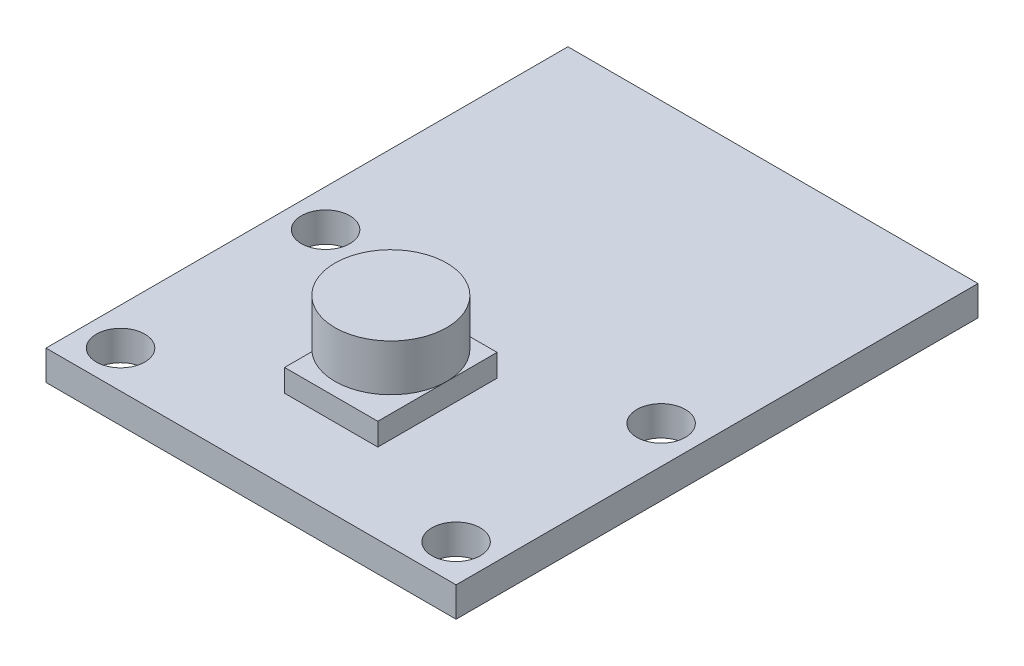
SolidWorks part; units mm, degrees
ref_plane "Plan de face" through (0, 0, 0) normal (0, 0, 1) x (1, 0, 0)
ref_plane "Plan de dessus" through (0, 0, 0) normal (0, 1, 0) x (1, 0, 0)
ref_plane "Plan de droite" through (0, 0, 0) normal (1, 0, 0) x (0, 0, -1)
sketch "Esquisse1" plane through (0, 0, 0) normal (0, 1, 0) x (1, 0, 0)
  line L0 (0, -7.5) -> (0, 20.5) construction
  line L1 (-11, 20.5) -> (11, 20.5)
  line L2 (-11, 20.5) -> (-11, -7.5)
  line L3 (-11, -7.5) -> (11, -7.5)
  line L4 (11, 20.5) -> (11, -7.5)
  line L5 (-7.7297, 0) -> (8.3243, 0) construction
  circle A0 centre (-9, 5.5) radius 1.3
  circle A1 centre (9, 5.5) radius 1.3
  circle A2 centre (9, -5.5) radius 1.3
  circle A3 centre (-9, -5.5) radius 1.3
  dimension "D6" = 2.6
  dimension "D1" = 11
  dimension "D2" = 28
  dimension "D3" = 22
  dimension "D4" = 18
  dimension "D5" = 7.5
extrude "Boss.-Extru.1" add sketch "Esquisse1" along normal blind 1.6
sketch "Esquisse2" plane through (0, 1.6, 0) normal (0, 1, 0) x (1, 0, 0)
  line L0 (-2.5, 3.2) -> (2.5, -3.2) construction
  line L1 (-2.5, 3.2) -> (2.5, 3.2)
  line L2 (-2.5, 3.2) -> (-2.5, -3.2)
  line L3 (-2.5, -3.2) -> (2.5, -3.2)
  line L4 (2.5, 3.2) -> (2.5, -3.2)
  dimension "D1" = 6.4
  dimension "D2" = 5
extrude "Boss.-Extru.2" add sketch "Esquisse2" along normal blind 1.2
sketch "Esquisse3" plane through (0, 2.8, 0) normal (0, 1, 0) x (1, 0, 0)
  circle A0 centre (0, 0) radius 3
  dimension "D1" = 6
extrude "Boss.-Extru.3" add sketch "Esquisse3" along normal blind 2.5 from offset 0.5 separate body
